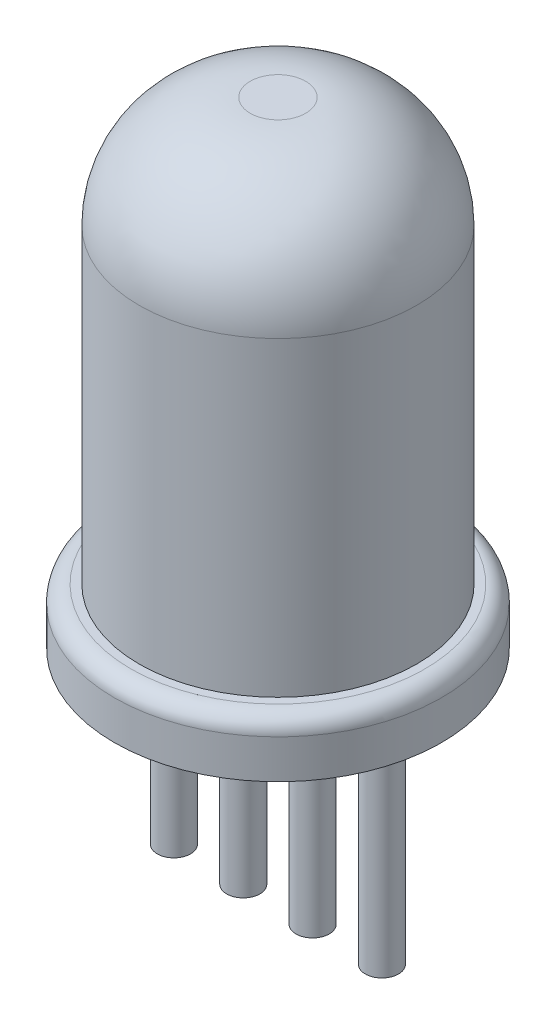
SolidWorks part; units mm, degrees
ref_plane "Спереди" through (0, 0, 0) normal (0, 0, 1) x (1, 0, 0)
ref_plane "Сверху" through (0, 0, 0) normal (0, 1, 0) x (1, 0, 0)
ref_plane "Справа" through (0, 0, 0) normal (1, 0, 0) x (0, 0, -1)
sketch "Эскиз1" plane through (0, 0, 0) normal (0, 1, 0) x (1, 0, 0)
  circle A0 centre (0, 0) radius 2.95
extrude "Бобышка-Вытянуть1" add sketch "Эскиз1" along normal blind 1 from offset 4
sketch "Эскиз3" plane through (0, 5, 0) normal (0, 1, 0) x (1, 0, 0)
  circle A0 centre (0, 0) radius 2.5
extrude "Бобышка-Вытянуть2" add sketch "Эскиз3" along normal blind 7.6
fillet "Скругление1" radius 2 1 edges at (0, 12.6, 2.5)
fillet "Скругление2" radius 0.3 1 edges at (0, 5, 2.95)
sketch "Эскиз4" plane through (0, 4, 0) normal (0, -1, 0) x (1, 0, 0)
  line L1 (-0.875, 0.25) -> (-0.375, 0.25)
  line L2 (-0.875, 0.25) -> (-0.875, -0.25)
  line L3 (-0.875, -0.25) -> (-0.375, -0.25)
  line L4 (-0.375, 0.25) -> (-0.375, -0.25)
  line L5 (-0.875, 0.25) -> (-0.375, -0.25) construction
  line L6 (-0.875, -0.25) -> (-0.375, 0.25) construction
  line L7 (-2.125, 0.25) -> (-1.625, 0.25)
  line L8 (-2.125, 0.25) -> (-2.125, -0.25)
  line L9 (-2.125, -0.25) -> (-1.625, -0.25)
  line L10 (-1.625, 0.25) -> (-1.625, -0.25)
  line L11 (-2.125, 0.25) -> (-1.625, -0.25) construction
  line L12 (-2.125, -0.25) -> (-1.625, 0.25) construction
  line L13 (0.375, 0.25) -> (0.875, 0.25)
  line L14 (0.375, 0.25) -> (0.375, -0.25)
  line L15 (0.375, -0.25) -> (0.875, -0.25)
  line L16 (0.875, 0.25) -> (0.875, -0.25)
  line L17 (0.375, 0.25) -> (0.875, -0.25) construction
  line L18 (0.375, -0.25) -> (0.875, 0.25) construction
  line L19 (1.625, 0.25) -> (2.125, 0.25)
  line L20 (1.625, 0.25) -> (1.625, -0.25)
  line L21 (1.625, -0.25) -> (2.125, -0.25)
  line L22 (2.125, 0.25) -> (2.125, -0.25)
  line L23 (1.625, 0.25) -> (2.125, -0.25) construction
  line L24 (1.625, -0.25) -> (2.125, 0.25) construction
  point P0 (-0.625, 0)
  point P5 (0, 0)
  point P6 (0.625, 0)
  point P8 (-1.875, 0)
  point P16 (0, 0)
  point P17 (0, 0)
  point P18 (0, 0)
  point P19 (0, 0)
  point P20 (0, 0)
  point P21 (1.875, 0)
  point P26 (0, 0)
  point P27 (0, 0)
  point P28 (0, 0)
  point P29 (0, 0)
  point P30 (0, 0)
  point P31 (0, 0)
  point P32 (0, 0)
  point P33 (0, 0)
sketch "Эскиз6" plane through (0, 0, 0) normal (0, 0, 1) x (1, 0, 0)
  line L0 (-0.625, 4) -> (-0.625, 0)
  line L1 (-1.875, 4) -> (-1.875, 0)
  line L2 (-2.125, 4) -> (-1.625, 4) construction
  point P0 (-0.625, 0)
  point P1 (-1.875, 0)
sweep "По траектории1" add path "Эскиз6" circular profile diameter 0.6 parameters "D3"=0.6
pattern_linear "Линейный массив1" count 4 spacing 1.25 along (1, 0, 0) of "По траектории1"
